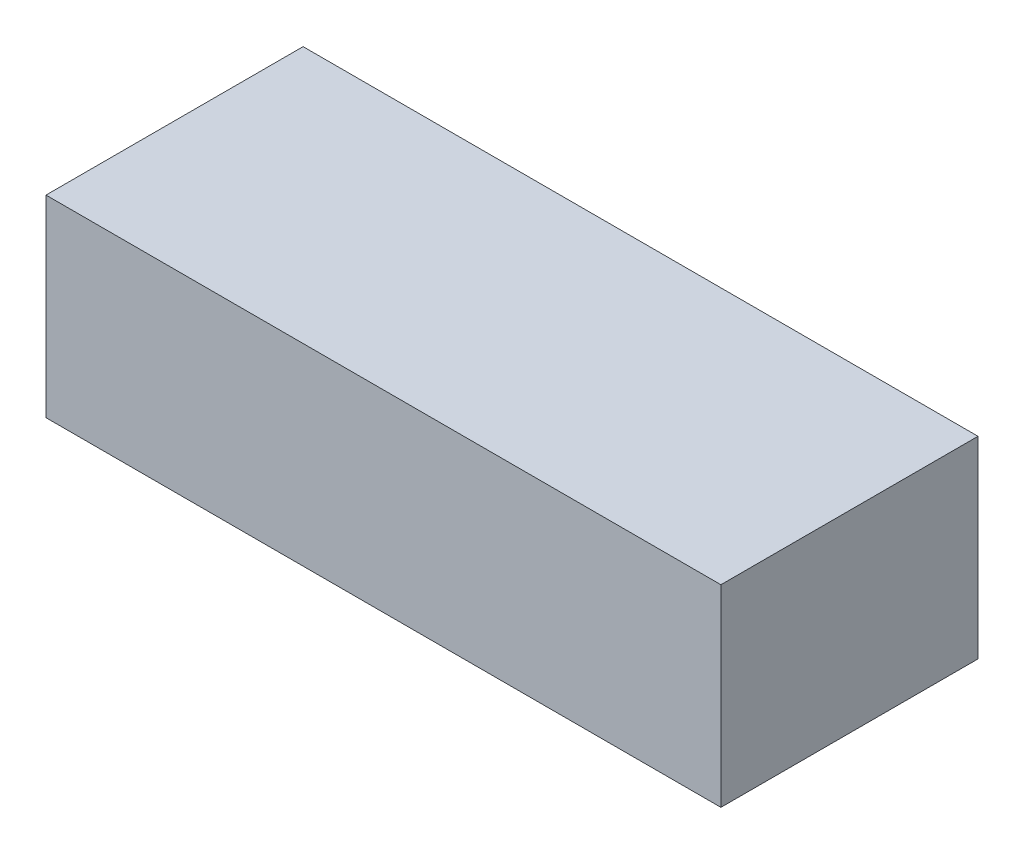
SolidWorks part; units mm, degrees
ref_plane "Front Plane" through (0, 0, 0) normal (0, 0, 1) x (1, 0, 0)
ref_plane "Top Plane" through (0, 0, 0) normal (0, 1, 0) x (1, 0, 0)
ref_plane "Right Plane" through (0, 0, 0) normal (1, 0, 0) x (0, 0, -1)
sketch "Sketch1" plane through (0, 0, 0) normal (0, 1, 0) x (1, 0, 0)
  line L1 (-10.1978, 4.3435) -> (10.8022, 4.3435)
  line L2 (-10.1978, 4.3435) -> (-10.1978, -3.6565)
  line L3 (-10.1978, -3.6565) -> (10.8022, -3.6565)
  line L4 (10.8022, 4.3435) -> (10.8022, -3.6565)
  dimension "D1" = 21
  dimension "D2" = 8
extrude "Boss-Extrude1" add sketch "Sketch1" along normal blind 6
